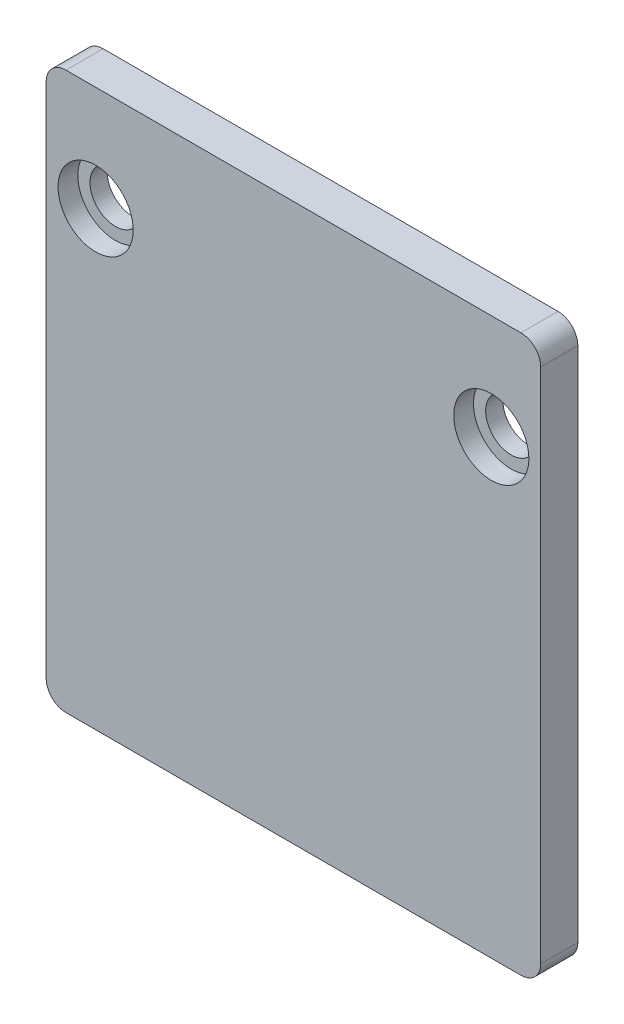
SolidWorks part; units mm, degrees
ref_plane "Front Plane" through (0, 0, 0) normal (0, 0, 1) x (1, 0, 0)
ref_plane "Top Plane" through (0, 0, 0) normal (0, 1, 0) x (1, 0, 0)
ref_plane "Right Plane" through (0, 0, 0) normal (1, 0, 0) x (0, 0, -1)
sketch "Sketch1" plane through (0, 0, 0) normal (0, 0, 1) x (1, 0, 0)
  line L1 (0, 0) -> (63.5, 0)
  line L2 (0, 0) -> (0, 71.4375)
  line L3 (0, 71.4375) -> (63.5, 71.4375)
  line L4 (63.5, 0) -> (63.5, 71.4375)
  dimension "D1" = 63.5
  dimension "D2" = 71.4375
extrude "Boss-Extrude1" add sketch "Sketch1" along normal blind 4.7625
hole_wizard "CBORE for 1/4 Socket Head Cap Screw1" positions "Sketch2" profile "Sketch4" counterbore size "1/4" standard "ANSI Inch" end condition through all
sketch "Sketch2" plane through (0, 0, 4.7625) normal (0, 0, 1) x (1, 0, 0)
  line L0 (31.75, 71.4375) -> (31.75, 0) construction
  line L1 (63.5, 71.4375) -> (0, 71.4375) construction
  line L2 (0, 0) -> (63.5, 0) construction
  point P9 (6.35, 57.9501)
  point P11 (57.15, 57.9501)
  dimension "D1" = 13.4874
  dimension "D2" = 13.4874
  dimension "D3" = 25.4
  dimension "D4" = 25.4
sketch "Sketch4" plane through (57.15, 57.9501, 4.7625) normal (1, 0, 0) x (0, -1, 0)
  line L0 (0, 0) -> (0, 4.7625)
  line L1 (0, 4.7625) -> (3.2639, 4.7625)
  line L3 (3.2639, 4.7625) -> (3.2639, 2.54)
  line L4 (3.2639, 2.54) -> (4.826, 2.54)
  line L5 (4.826, 2.54) -> (4.826, 0)
  line L7 (4.826, 0) -> (0, 0)
  line L11 (0, -6.35) -> (0, 107.95) construction
  dimension "Thru Hole Dia." = 6.5278
  dimension "Thru Hole Depth" = 4.7625
  dimension "C'Bore Dia." = 9.652
  dimension "C'Bore Depth" = 2.54
fillet "Fillet2" radius 2.54 4 edges at (0, 0, 2.3813) (63.5, 0, 2.3813) (63.5, 71.4375, 2.3813) (0, 71.4375, 2.3813)
